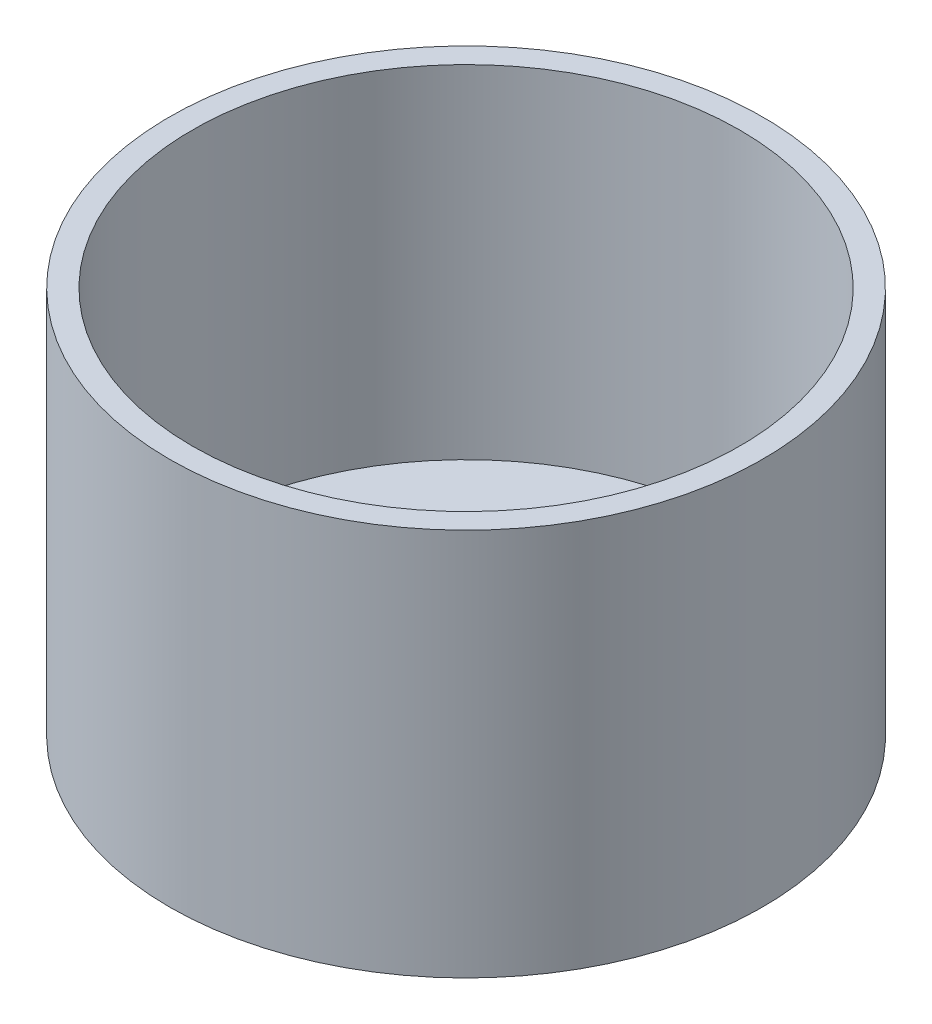
SolidWorks part; units mm, degrees
ref_plane "Front Plane" through (0, 0, 0) normal (0, 0, 1) x (1, 0, 0)
ref_plane "Top Plane" through (0, 0, 0) normal (0, 1, 0) x (1, 0, 0)
ref_plane "Right Plane" through (0, 0, 0) normal (1, 0, 0) x (0, 0, -1)
sketch "Sketch1" plane through (0, 0, 0) normal (0, 1, 0) x (1, 0, 0)
  circle A0 centre (0, 0) radius 13
  dimension "D1" = 26
extrude "Boss-Extrude2" add sketch "Sketch1" along normal blind 2
sketch "Sketch2" plane through (0, 2, 0) normal (0, 1, 0) x (1, 0, 0)
  circle A0 centre (0, 0) radius 12
  circle A1 centre (0, 0) radius 13 construction
  circle A2 centre (0, 0) radius 13
  dimension "D1" = 24
extrude "Boss-Extrude3" add sketch "Sketch2" along normal blind 15
sketch "Sketch3" plane through (0, 0, 0) normal (0, -1, 0) x (1, 0, 0)
  circle A0 centre (0, 0) radius 5
  dimension "D1" = 10
extrude "Cut-Extrude1" cut sketch "Sketch3" against normal blind 15
